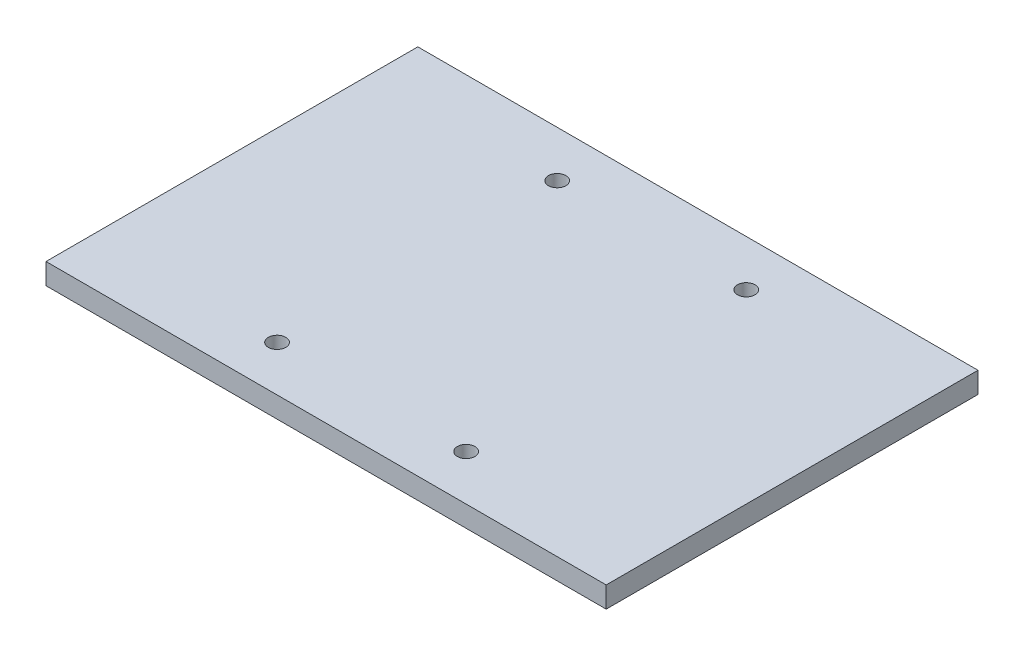
SolidWorks part; units mm, degrees
ref_plane "Ebene vorne" through (0, 0, 0) normal (0, 0, 1) x (1, 0, 0)
ref_plane "Ebene oben" through (0, 0, 0) normal (0, 1, 0) x (1, 0, 0)
ref_plane "Ebene rechts" through (0, 0, 0) normal (1, 0, 0) x (0, 0, -1)
sketch "Skizze7" plane through (0, 0, 0) normal (0, 1, 0) x (1, 0, 0)
  line L1 (0, 0) -> (80, 0)
  line L2 (0, 0) -> (0, 53.1)
  line L3 (0, 53.1) -> (80, 53.1)
  line L4 (80, 0) -> (80, 53.1)
  dimension "D1" = 80
  dimension "D2" = 53.1
extrude "Aufsatz-Linear austragen2" add sketch "Skizze7" along normal blind 3
hole_wizard "M3 Gewindebohrung2" positions "Skizze8" profile "Skizze9" tap size "M3" standard "DIN" end condition up to next
sketch "Skizze8" plane through (0, 3, 0) normal (0, 1, 0) x (1, 0, 0)
  line L0 (0, 0) -> (80, 0) construction
  line L1 (0, 53.1) -> (0, 0) construction
  point P0 (26.5, 6.5)
  point P2 (26.5, 46.5)
  point P4 (53.5, 46.5)
  point P6 (53.5, 6.5)
  dimension "D1" = 6.5
  dimension "D2" = 26.5
  dimension "D3" = 27
  dimension "D4" = 40
sketch "Skizze9" plane through (26.5, 3, -6.5) normal (1, 0, 0) x (0, 0, 1)
  line L0 (0, 0) -> (0, 3)
  line L1 (0, 3) -> (1.25, 3)
  line L2 (1.25, 3) -> (1.25, 0)
  line L5 (1.25, 0) -> (0, 0)
  line L11 (0, -6.35) -> (0, 107.95) construction
  dimension "Bohrerdurchmesser" = 2.5
  dimension "Bohrungstiefe" = 3
cosmetic thread "Bohrungsgewinde1"
cosmetic thread "Bohrungsgewinde2"
cosmetic thread "Bohrungsgewinde3"
cosmetic thread "Bohrungsgewinde4"
